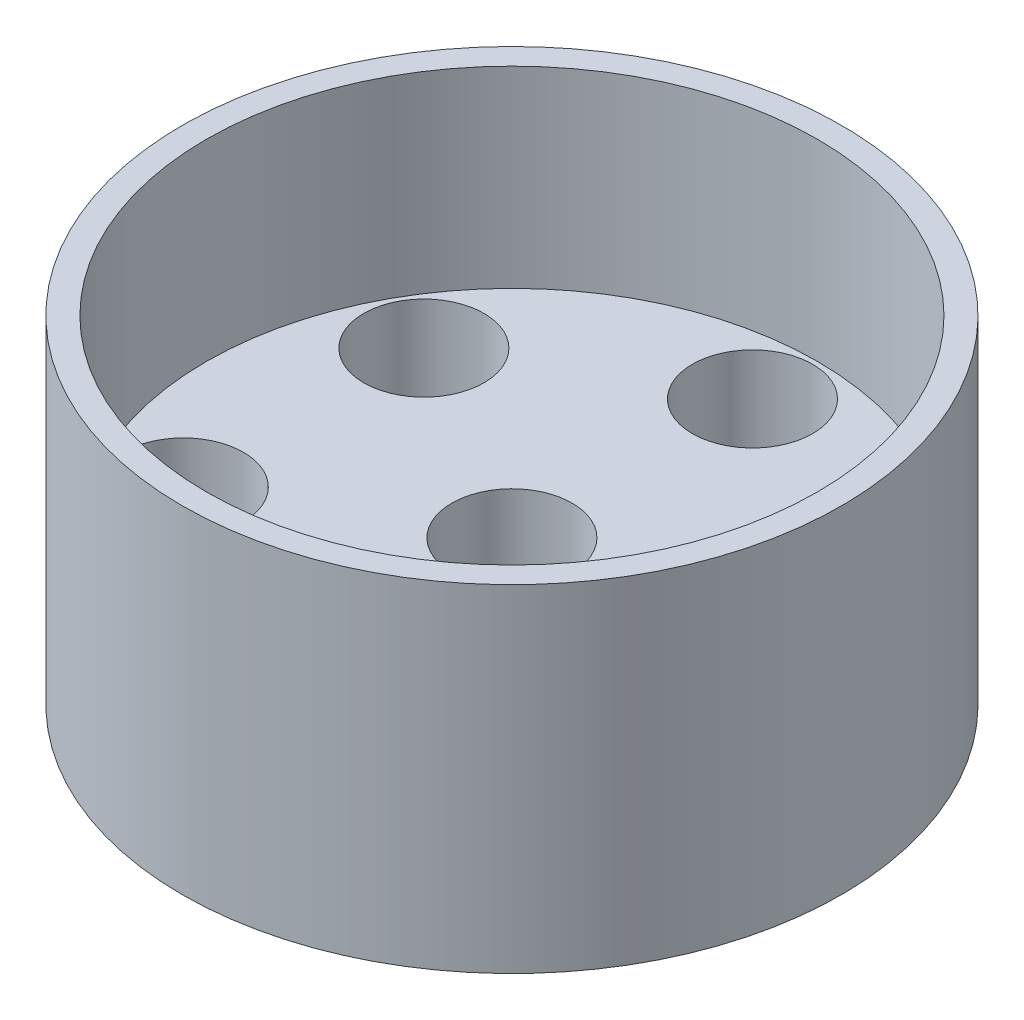
SolidWorks part; units mm, degrees
ref_plane "Front Plane" through (0, 0, 0) normal (0, 0, 1) x (1, 0, 0)
ref_plane "Top Plane" through (0, 0, 0) normal (0, 1, 0) x (1, 0, 0)
ref_plane "Right Plane" through (0, 0, 0) normal (1, 0, 0) x (0, 0, -1)
sketch "Sketch1" plane through (0, 0, 0) normal (0, 1, 0) x (1, 0, 0)
  circle A0 centre (0, 0) radius 2.5
  circle A1 centre (0, 0) radius 13.1
  circle A2 centre (0, 0) radius 14
  dimension "D1" = 5
  dimension "D2" = 26.2
  dimension "D3" = 28
extrude "Boss-Extrude1" add sketch "Sketch1" along normal blind 6 contours A1 A0
sketch "Sketch2" plane through (0, 6, 0) normal (0, 1, 0) x (1, 0, 0)
  circle A0 centre (0, 0) radius 13.7
  circle A1 centre (0, 0) radius 12.7
  dimension "D1" = 27.4
  dimension "D2" = 25.4
extrude "Boss-Extrude2" add sketch "Sketch2" along normal blind 8 and the other way up to surface other way up to face at (0, 0, 2.5)
sketch "Sketch7" plane through (0, 6, 0) normal (0, 1, 0) x (1, 0, 0)
  circle A0 centre (0, 10) radius 2.5
  circle A1 centre (8.6603, 5) radius 2.5
  circle A2 centre (8.6603, -5) radius 2.5
  circle A3 centre (0, -10) radius 2.5
  circle A4 centre (-8.6603, -5) radius 2.5
  circle A5 centre (-8.6603, 5) radius 2.5
  point P3 (0, 0)
  point P15 (0, 0)
  dimension "D1" = 5
  dimension "D2" = 10
  dimension "D3" = 0
  dimension "D5" = 8.6603
  dimension "D6" = 5
  dimension "D4" = 6
extrude "Cut-Extrude4" cut sketch "Sketch7" against normal up to surface (6 mm away) contours A0 | A1 | A2 | A3 | A4 | A5 up to face at (0, 0, 2.5)
